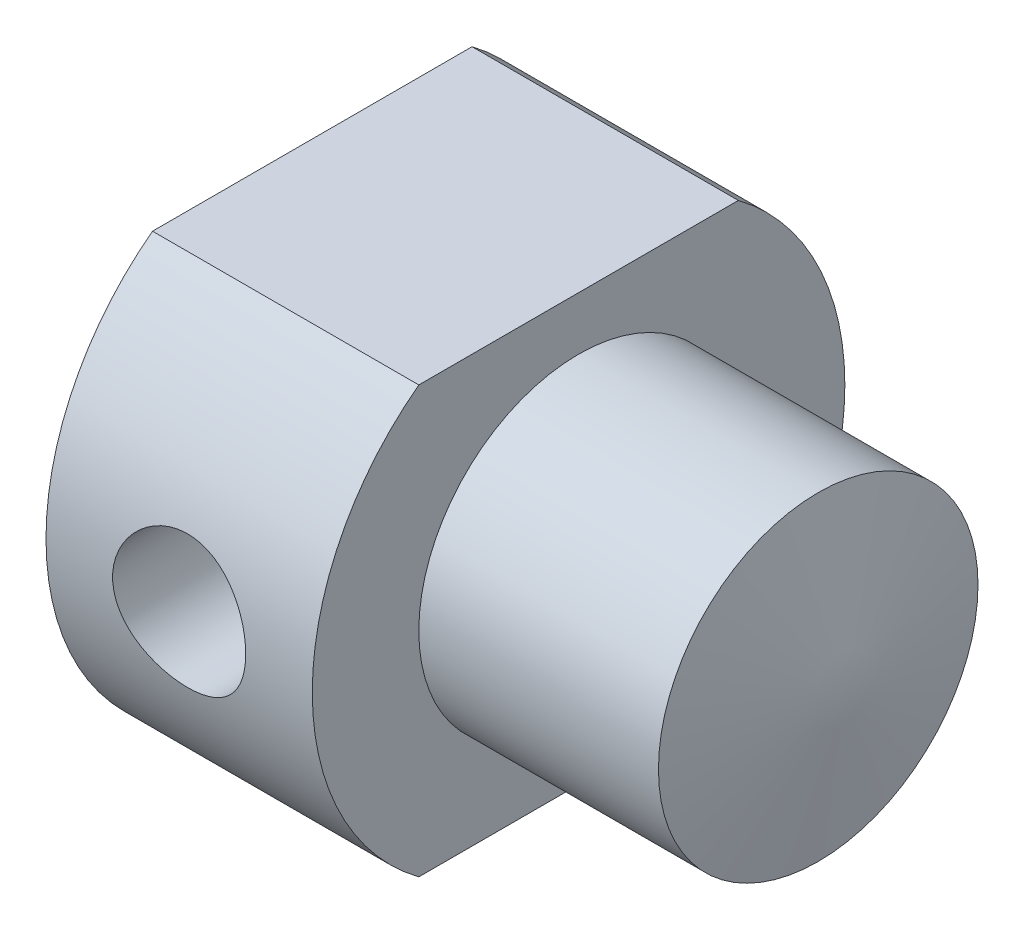
SolidWorks part; units mm, degrees
material "PBT Общее назначение"
ref_plane "Спереди" through (0, 0, 0) normal (0, 0, 1) x (1, 0, 0)
ref_plane "Сверху" through (0, 0, 0) normal (0, 1, 0) x (1, 0, 0)
ref_plane "Справа" through (0, 0, 0) normal (1, 0, 0) x (0, 0, -1)
sketch "Эскиз1" plane through (0, 0, 0) normal (0, 0, 1) x (1, 0, 0)
  line L0 (0, 0) -> (-70.4249, 0) construction
  line L1 (0, 0) -> (-1.058, 6)
  line L2 (-1.058, 6) -> (-10.058, 6)
  line L3 (-10.058, 6) -> (-10.058, 10)
  line L4 (-10.058, 10) -> (-20.058, 10)
  line L5 (-20.058, 10) -> (-20.058, 0)
  line L6 (-20.058, 0) -> (0, 0)
  dimension "D1" = 80
  dimension "D2" = 6
  dimension "D3" = 9
  dimension "D4" = 10
  dimension "D5" = 10
  dimension "D6" = 20.058
revolve "Повернуть1" add sketch "Эскиз1" angle 360 about L0
sketch "Эскиз2" plane through (0, 0, 0) normal (0, 0, 1) x (1, 0, 0)
  line L0 (0, 0) -> (-15.058, 0) construction
  line L1 (-15.058, 0) -> (-15.058, 10) construction
  line L2 (-10.058, 10) -> (-20.058, 10) construction
  line L3 (-21.8031, -15.6813) -> (-21.8031, -8)
  line L4 (-21.8031, 15.6813) -> (-8.0698, 15.6813)
  line L5 (-21.8031, 15.6813) -> (-21.8031, 8)
  line L6 (-21.8031, 8) -> (-8.0698, 8)
  line L7 (-8.0698, 15.6813) -> (-8.0698, 8)
  line L8 (-21.8031, -8) -> (-8.0698, -8)
  line L9 (-8.0698, -15.6813) -> (-8.0698, -8)
  line L10 (-21.8031, -15.6813) -> (-8.0698, -15.6813)
  circle A0 centre (-15.058, 0) radius 2.5
  point P15 (-7.9505, 12.6813)
  dimension "D1" = 5
  dimension "D2" = 8
extrude "Вырез-Вытянуть1" cut sketch "Эскиз2" against normal mid plane 30
